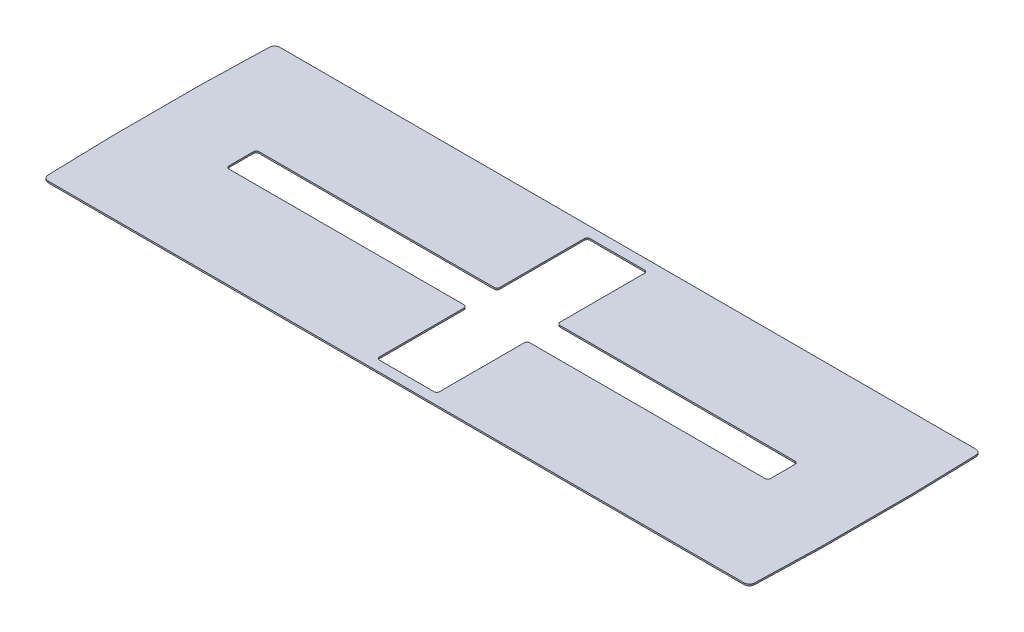
SolidWorks part; units mm, degrees
material "ASTM A36 Steel"
ref_plane "Front Plane" through (0, 0, 0) normal (0, 0, 1) x (1, 0, 0)
ref_plane "Top Plane" through (0, 0, 0) normal (0, 1, 0) x (1, 0, 0)
ref_plane "Right Plane" through (0, 0, 0) normal (1, 0, 0) x (0, 0, -1)
sketch "Sketch1" plane through (0, 0, 0) normal (0, 1, 0) x (1, 0, 0)
  line L1 (596.9, -193.04) -> (-596.9, -193.04)
  line L2 (596.9, -193.04) -> (596.9, 193.04)
  line L3 (596.9, 193.04) -> (-596.9, 193.04)
  line L4 (-596.9, -193.04) -> (-596.9, 193.04)
  line L5 (596.9, -193.04) -> (-596.9, 193.04) construction
  line L6 (596.9, 193.04) -> (-596.9, -193.04) construction
  point P0 (0, 0)
  dimension "D1" = 1193.8
  dimension "D2" = 386.08
extrude "Boss-Extrude1" add sketch "Sketch1" along normal blind 2.667
sketch "Sketch2" plane through (0, 2.667, 0) normal (0, 1, 0) x (1, 0, 0)
  line L0 (592.1375, -38.1) -> (-592.1375, -38.1) construction
  line L1 (592.1375, -38.1) -> (-592.1375, -38.1) construction
  line L2 (592.1375, 38.1) -> (-592.1375, 38.1) construction
  line L3 (592.1375, 38.1) -> (-592.1375, 38.1) construction
  line L4 (0, -38.1) -> (0, 38.1) construction
  line L5 (0, 0) -> (457.2, 0) construction
  line L6 (-457.2, 25.4) -> (-457.2, -25.4)
  line L7 (-457.2, 25.4) -> (457.2, 25.4)
  line L8 (0, 25.4) -> (0, -25.4)
  line L9 (-457.2, -25.4) -> (457.2, -25.4)
  line L10 (457.2, 25.4) -> (457.2, -25.4)
  line L11 (0, 25.4) -> (457.2, -25.4) construction
  line L12 (0, -25.4) -> (457.2, 25.4) construction
  point P8 (228.6, 0)
  dimension "D1" = 457.2
  dimension "D2" = 50.8
extrude "Cut-Extrude1" cut sketch "Sketch2" against normal through all contours L10 L7 L8 L9 | L6 L9 L8 L7
sketch "Sketch3" plane through (0, 2.667, 0) normal (0, 1, 0) x (1, 0, 0)
  line L0 (-101.6, -190.6168) -> (-101.6, 190.3832) construction
  line L1 (-101.6, -190.6168) -> (-101.6, 190.3832) construction
  line L2 (101.6, -190.6168) -> (101.6, 190.3832) construction
  line L3 (101.6, -190.6168) -> (101.6, 190.3832) construction
  line L5 (-50.8, 177.8) -> (50.8, 177.8)
  line L6 (-50.8, 177.8) -> (-50.8, -177.8)
  line L7 (-50.8, -177.8) -> (50.8, -177.8)
  line L8 (50.8, 177.8) -> (50.8, -177.8)
  line L9 (-50.8, 177.8) -> (50.8, -177.8) construction
  line L10 (-50.8, -177.8) -> (50.8, 177.8) construction
  point P4 (0, 0)
  dimension "D1" = 355.6
  dimension "D2" = 101.6
extrude "Cut-Extrude2" cut sketch "Sketch3" against normal through all
fillet "Fillet1" radius 4.7625 12 edges at (-457.2, 1.3335, -25.4) (-457.2, 1.3335, 25.4) (457.2, 1.3335, -25.4) (457.2, 1.3335, 25.4) (-50.8, 1.3335, -25.4) (-50.8, 1.3335, 25.4) (50.8, 1.3335, 25.4) (50.8, 1.3335, -25.4) (50.8, 1.3335, 177.8) (-50.8, 1.3335, 177.8) (-50.8, 1.3335, -177.8) (50.8, 1.3335, -177.8)
sketch "Sketch4" plane through (0, 0, 0) normal (0, -1, 0) x (1, 0, 0)
  line L0 (-593.8929, 186.8625) -> (-596.9, 76.2) construction
  line L1 (-593.8929, -186.8625) -> (-596.9, -76.2) construction
  line L2 (-593.8929, 186.8625) -> (-596.9, 76.2)
  line L3 (-593.8929, -186.8625) -> (-596.9, -76.2)
  line L4 (593.8929, 186.8625) -> (596.9, 76.2) construction
  line L5 (593.8929, -186.8625) -> (596.9, -76.2) construction
  line L6 (593.8929, 186.8625) -> (596.9, 76.2)
  line L7 (593.8929, -186.8625) -> (596.9, -76.2)
  arc A0 (-593.8929, -186.8625) -> (-587.5452, -193.04) centre (-587.5452, -186.69) ccw construction
  arc A1 (-587.5452, 193.04) -> (-593.8929, 186.8625) centre (-587.5452, 186.69) ccw construction
  arc A2 (-593.8929, -186.8625) -> (-587.5452, -193.04) centre (-587.5452, -186.69) ccw
  arc A3 (-587.5452, 193.04) -> (-593.8929, 186.8625) centre (-587.5452, 186.69) ccw
  arc A4 (593.8929, 186.8625) -> (587.5452, 193.04) centre (587.5452, 186.69) ccw construction
  arc A5 (587.5452, -193.04) -> (593.8929, -186.8625) centre (587.5452, -186.69) ccw construction
  arc A6 (593.8929, 186.8625) -> (587.5452, 193.04) centre (587.5452, 186.69) ccw
  arc A7 (587.5452, -193.04) -> (593.8929, -186.8625) centre (587.5452, -186.69) ccw
  line M25 (-596.9, 193.04) -> (-596.9, -193.04)
  line M26 (-596.9, -193.04) -> (596.9, -193.04)
  line M27 (596.9, -193.04) -> (596.9, 193.04)
  line M28 (596.9, 193.04) -> (-596.9, 193.04)
extrude "Cut-Extrude3" cut sketch "Sketch4" against normal through all contours A2 L3 M25 M26 | A3 L2 M28 M25 | A6 L6 M27 M28 | A7 L7 M26 M27
sketch "Sketch5" plane through (0, 2.667, 0) normal (0, 1, 0) x (1, 0, 0)
  line L0 (587.5452, 195.58) -> (-587.5452, 195.58)
  line L1 (-596.4319, 186.9315) -> (-599.44, 76.2345)
  line L2 (-599.44, 76.2345) -> (-599.44, -76.2345)
  line L3 (-599.44, -76.2345) -> (-596.4319, -186.9315)
  line L4 (-587.5452, -195.58) -> (587.5452, -195.58)
  line L5 (596.4319, -186.9315) -> (599.44, -76.2345)
  line L6 (599.44, -76.2345) -> (599.44, 76.2345)
  line L7 (599.44, 76.2345) -> (596.4319, 186.9315)
  line L8 (596.9, 76.2) -> (593.8929, 186.8625)
  line L9 (587.5452, 193.04) -> (-587.5452, 193.04)
  line L10 (-593.8929, 186.8625) -> (-596.9, 76.2)
  line L11 (-596.9, 76.2) -> (-596.9, -76.2)
  line L12 (-596.9, -76.2) -> (-593.8929, -186.8625)
  line L13 (-587.5452, -193.04) -> (587.5452, -193.04)
  line L14 (593.8929, -186.8625) -> (596.9, -76.2)
  line L15 (596.9, -76.2) -> (596.9, 76.2)
  line L16 (596.9, 76.2) -> (593.8929, 186.8625)
  line L17 (587.5452, 193.04) -> (-587.5452, 193.04)
  line L18 (-593.8929, 186.8625) -> (-596.9, 76.2)
  line L19 (-596.9, 76.2) -> (-596.9, -76.2)
  line L20 (-596.9, -76.2) -> (-593.8929, -186.8625)
  line L21 (-587.5452, -193.04) -> (587.5452, -193.04)
  line L22 (593.8929, -186.8625) -> (596.9, -76.2)
  line L23 (596.9, -76.2) -> (596.9, 76.2)
  arc A0 (-587.5452, 195.58) -> (-596.4319, 186.9315) centre (-587.5452, 186.69) ccw
  arc A1 (-596.4319, -186.9315) -> (-587.5452, -195.58) centre (-587.5452, -186.69) ccw
  arc A2 (587.5452, -195.58) -> (596.4319, -186.9315) centre (587.5452, -186.69) ccw
  arc A3 (596.4319, 186.9315) -> (587.5452, 195.58) centre (587.5452, 186.69) ccw
  arc A4 (593.8929, 186.8625) -> (587.5452, 193.04) centre (587.5452, 186.69) ccw
  arc A5 (-587.5452, 193.04) -> (-593.8929, 186.8625) centre (-587.5452, 186.69) ccw
  arc A6 (-593.8929, -186.8625) -> (-587.5452, -193.04) centre (-587.5452, -186.69) ccw
  arc A7 (587.5452, -193.04) -> (593.8929, -186.8625) centre (587.5452, -186.69) ccw
  arc A8 (593.8929, 186.8625) -> (587.5452, 193.04) centre (587.5452, 186.69) ccw
  arc A9 (-587.5452, 193.04) -> (-593.8929, 186.8625) centre (-587.5452, 186.69) ccw
  arc A10 (-593.8929, -186.8625) -> (-587.5452, -193.04) centre (-587.5452, -186.69) ccw
  arc A11 (587.5452, -193.04) -> (593.8929, -186.8625) centre (587.5452, -186.69) ccw
  dimension "D1" = 0
  dimension "D2" = 2.54
extrude "Boss-Extrude2" add sketch "Sketch5" against normal up to surface (2.667 mm away) up to face at (0, 0, 0)
